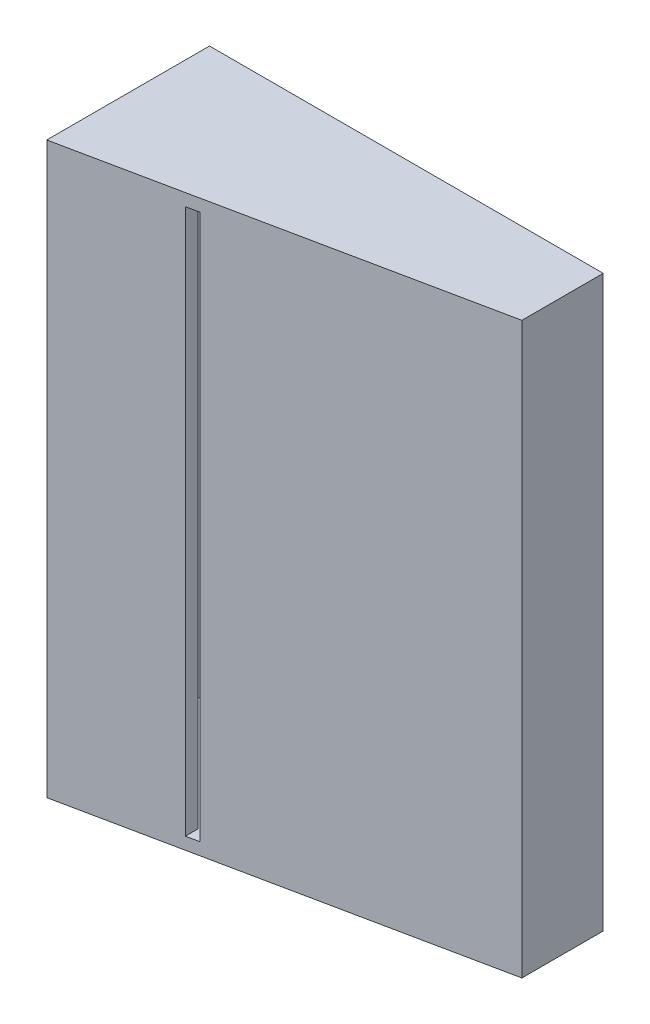
SolidWorks part; units mm, degrees
ref_plane "Front Plane" through (0, 0, 0) normal (0, 0, 1) x (1, 0, 0)
ref_plane "Top Plane" through (0, 0, 0) normal (0, 1, 0) x (1, 0, 0)
ref_plane "Right Plane" through (0, 0, 0) normal (1, 0, 0) x (0, 0, -1)
sketch "Sketch1" plane through (0, 0, 0) normal (0, 0, 1) x (1, 0, 0)
  line L3 (-46.8875, 15.35) -> (-46.8875, 35.15)
  line L6 (-46.8875, 35.15) -> (-43.9875, 35.15)
  line L7 (-43.9875, 15.35) -> (-46.8875, 15.35)
  line L8 (-43.9875, 35.15) -> (-43.9875, 15.35)
  line L9 (-46.8875, 35.15) -> (-43.9875, 35.15)
  line L10 (-43.9875, 15.35) -> (-46.8875, 15.35)
  line L11 (-43.9875, 35.15) -> (-43.9875, 15.35)
  dimension "D1" = 0.1
extrude "Boss-Extrude1" add sketch "Sketch1" against normal up to surface (1.5 mm away)
sketch "Sketch2" plane through (0, 0, -1.5) normal (0, 0, -1) x (-1, 0, 0)
  line L0 (46.8875, 15.35) -> (46.8875, 35.15) construction
  line L1 (24.3875, 12.25) -> (46.8875, 12.25)
  line L2 (24.3875, 12.25) -> (24.3875, 38.25)
  line L3 (24.3875, 38.25) -> (46.8875, 38.25)
  line L4 (46.8875, 12.25) -> (46.8875, 38.25)
  line L5 (24.3875, 12.25) -> (46.8875, 38.25) construction
  line L6 (24.3875, 38.25) -> (46.8875, 12.25) construction
  line L7 (43.8875, 35.25) -> (43.8875, 15.25) construction
  line L8 (46.8875, 35.25) -> (43.8875, 35.25) construction
  line L9 (24.3875, 26.75) -> (24.3875, 23.75) construction
  point P0 (35.6375, 25.25)
  point P7 (0, 0)
  point P10 (43.8875, 25.25)
  dimension "D1" = 3
extrude "Boss-Extrude3" add sketch "Sketch2" along normal blind 1.5
sketch "Sketch3" plane through (0, 0, 0) normal (0, 0, 1) x (1, 0, 0)
  line L0 (-46.8875, 15.25) -> (-46.8875, 35.25)
  line L8 (-43.8875, 35.25) -> (-43.8875, 15.25)
  line L9 (-43.8875, 15.25) -> (-46.8875, 15.25)
  line L10 (-46.8875, 15.25) -> (-46.8875, -9.75)
  line L11 (-46.8875, -9.75) -> (1.5, -9.75)
  line L12 (1.5, -9.75) -> (1.5, 60.25)
  line L13 (1.5, 60.25) -> (-46.8875, 60.25)
  line L14 (-46.8875, 60.25) -> (-46.8875, 35.25)
  line L15 (-46.8875, 35.25) -> (-43.8875, 35.25)
  line L18 (-46.8875, 15.25) -> (-46.8875, -9.75)
  line L19 (-46.8875, -9.75) -> (1.5, -9.75)
  line L20 (1.5, -9.75) -> (1.5, 60.25)
  line L21 (1.5, 60.25) -> (-46.8875, 60.25)
  line L22 (-46.8875, 60.25) -> (-46.8875, 35.25)
  dimension "D1" = 0
extrude "Boss-Extrude4" add sketch "Sketch3" along normal blind 20
sketch "Sketch4" plane through (0, -9.75, 0) normal (0, -1, 0) x (1, 0, 0)
  line L0 (-46.8875, 20) -> (1.5, 10)
  line L1 (1.5, 10) -> (1.5, 20)
  line L2 (1.5, 20) -> (-46.8875, 20)
  line L3 (1.5, 20) -> (1.5, 0) construction
  point P4 (1.5, 0)
  point P7 (1.5, 4.5035)
  dimension "D1" = 10
extrude "Cut-Extrude1" cut sketch "Sketch4" against normal up to surface (70 mm away) up to face at (-22.6937, 60.25, 10)
ref_plane "Plane1" through (0, 25.25, 0) normal (0, 1, 0) x (1, 0, 0)
sketch "Sketch5" plane through (0, -9.75, 0) normal (0, -1, 0) x (1, 0, 0)
  line L4 (-46.8875, 20) -> (-46.8875, 0) construction
  line L8 (0, 1.5) -> (0, 8.7783)
  line L9 (0, 8.7783) -> (-45.3875, 18.1583)
  line L10 (-45.3875, 18.1583) -> (-45.3875, 1.5)
  line L11 (-45.3875, 1.5) -> (0, 1.5)
  line L12 (0, 1.5) -> (0, 8.7783)
  line L13 (0, 8.7783) -> (-46.8875, 18.4683)
  line L14 (-46.8875, 18.4683) -> (-46.8875, 1.5)
  line L15 (-46.8875, 1.5) -> (0, 1.5)
  dimension "D1" = 1.5
extrude "Cut-Extrude2" cut sketch "Sketch5" along normal up to surface (33.5 mm away) from offset 1.5
mirror "Mirror1" about plane through (0, 25.25, 0) normal (0, 1, 0) of "Cut-Extrude2"
sketch "Sketch6" plane through (0, 0, 0) normal (0, 0, -1) x (-1, 0, 0)
  line L0 (11, 25.25) -> (-11, 25.25) construction
  line L1 (32.77, 58.75) -> (31.27, 58.75)
  line L2 (32.77, 58.75) -> (32.77, -8.25)
  line L3 (32.77, -8.25) -> (31.27, -8.25)
  line L4 (31.27, 58.75) -> (31.27, -8.25)
  line L5 (32.77, 58.75) -> (31.27, -8.25) construction
  line L6 (32.77, -8.25) -> (31.27, 58.75) construction
  line L8 (46.8875, 58.75) -> (0, 58.75) construction
  line L9 (0, 58.75) -> (0, -8.25) construction
  point P0 (32.02, 25.25)
  point P5 (0, 0)
  dimension "D1" = 1.5
  dimension "D2" = 31.27
extrude "Cut-Extrude3" cut sketch "Sketch6" against normal up to surface (17.0824 mm away)
